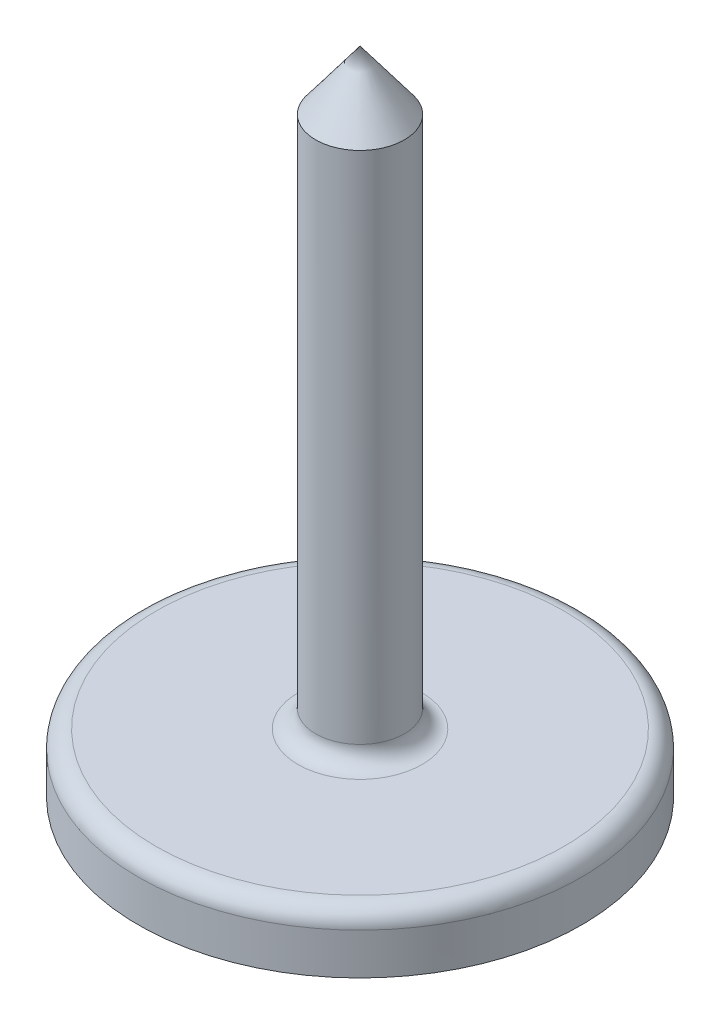
SolidWorks part; units mm, degrees
ref_plane "Front Plane" through (0, 0, 0) normal (0, 0, 1) x (1, 0, 0)
ref_plane "Top Plane" through (0, 0, 0) normal (0, 1, 0) x (1, 0, 0)
ref_plane "Right Plane" through (0, 0, 0) normal (1, 0, 0) x (0, 0, -1)
sketch "Çizim1" plane through (0, 0, 0) normal (0, 0, 1) x (1, 0, 0)
  line L0 (0, 0) -> (37.5, 0)
  line L1 (37.5, 0) -> (37.5, 10)
  line L2 (37.5, 10) -> (7.5, 10)
  line L3 (0, 0) -> (0, 110)
  line L5 (7.5, 100) -> (7.5, 10)
  line L6 (0, 110) -> (7.5, 100)
  dimension "D1" = 10
  dimension "D2" = 37.5
  dimension "D3" = 7.5
  dimension "D4" = 110
  dimension "D5" = 90
revolve "Döndür1" add sketch "Çizim1" angle 360 about L3
fillet "Radyus1" radius 3 2 edges at (0, 10, -7.5) (0, 10, -37.5)
